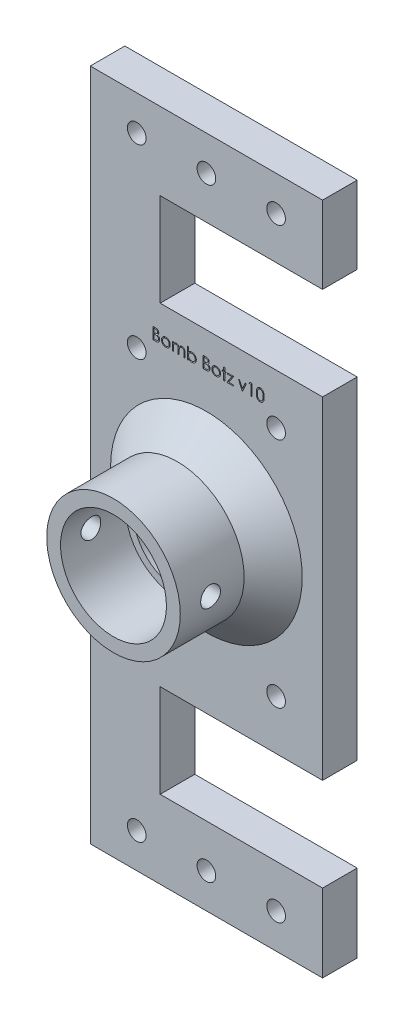
SolidWorks part; units mm, degrees
ref_plane "Front Plane" through (0, 0, 0) normal (0, 0, 1) x (1, 0, 0)
ref_plane "Top Plane" through (0, 0, 0) normal (0, 1, 0) x (1, 0, 0)
ref_plane "Right Plane" through (0, 0, 0) normal (1, 0, 0) x (0, 0, -1)
sketch "Sketch1" plane through (0, 0, 0) normal (0, 0, 1) x (1, 0, 0)
  line L5 (-31.75, 92.075) -> (31.75, 92.075)
  line L6 (-31.75, 92.075) -> (-31.75, -92.075)
  line L7 (-31.75, -92.075) -> (31.75, -92.075)
  line L8 (31.75, 92.075) -> (31.75, -92.075)
  line L9 (-31.75, 92.075) -> (31.75, -92.075) construction
  line L10 (-31.75, -92.075) -> (31.75, 92.075) construction
  point P5 (0, 0)
  dimension "D1" = 63.5
  dimension "D2" = 184.15
extrude "Boss-Extrude1" add sketch "Sketch1" along normal blind 4.7625 and the other way blind 4.699
sketch "Sketch3" plane through (0, 0, 4.7625) normal (0, 0, 1) x (1, 0, 0)
  circle A0 centre (0, 0) radius 6.35
  dimension "D1" = 12.7
extrude "Cut-Extrude1" cut sketch "Sketch3" against normal blind 0.508
sketch "Sketch4" plane through (0, 0, 4.7625) normal (0, 0, 1) x (1, 0, 0)
  circle A0 centre (0, 0) radius 18.2562
  dimension "D1" = 36.5125
extrude "Boss-Extrude2" add sketch "Sketch4" along normal blind 38.1 contours A0
sketch "Sketch5" plane through (0, 0, 42.8625) normal (0, 0, 1) x (1, 0, 0)
  circle A0 centre (0, 0) radius 12.4619
  dimension "D1" = 24.9237
extrude "Cut-Extrude2" cut sketch "Sketch5" against normal blind 38.1 contours A0
sketch "Sketch7" plane through (0, 0, 42.8625) normal (0, 0, 1) x (1, 0, 0)
  circle A0 centre (0, 0) radius 14.2875
  dimension "D1" = 28.575
extrude "Cut-Extrude3" cut sketch "Sketch7" against normal blind 30.48
hole_wizard "#10 Clearance Hole1" positions "Sketch8" profile "Sketch9" hole size "#10" standard "ANSI Inch" end condition up to next
sketch "Sketch8" plane through (0, 0, 4.7625) normal (0, 0, 1) x (1, 0, 0)
  line L0 (31.75, 92.075) -> (-31.75, 92.075) construction
  line L1 (31.75, -92.075) -> (31.75, 92.075) construction
  line L2 (-31.75, 92.075) -> (-31.75, -92.075) construction
  line L3 (-31.75, -92.075) -> (31.75, -92.075) construction
  point P0 (-19.05, 82.55)
  point P2 (-19.05, -82.55)
  point P4 (19.05, -82.55)
  point P6 (19.05, 82.55)
  point P23 (-19.05, 31.75)
  point P26 (-19.05, -31.75)
  point P28 (19.05, -31.75)
  point P30 (19.05, 31.75)
  point P31 (0, 82.55)
  point P33 (0, -82.55)
  dimension "D1" = 9.525
  dimension "D2" = 12.7
  dimension "D3" = 9.525
  dimension "D4" = 12.7
  dimension "D5" = 9.525
  dimension "D6" = 12.7
  dimension "D7" = 12.7
  dimension "D8" = 9.525
  dimension "D11" = 50.8
  dimension "D12" = 50.8
  dimension "D13" = 50.8
  dimension "D14" = 50.8
sketch "Sketch9" plane through (-19.05, 82.55, 4.7625) normal (1, 0, 0) x (0, -1, 0)
  line L0 (0, 0) -> (0, 9.4615)
  line L1 (0, 9.4615) -> (2.5527, 9.4615)
  line L2 (2.5527, 9.4615) -> (2.5527, 0)
  line L5 (2.5527, 0) -> (0, 0)
  line L11 (0, -6.35) -> (0, 107.95) construction
  dimension "Thru Hole Dia." = 5.1054
  dimension "Thru Hole Depth" = 9.4615
sketch "Sketch10" plane through (0, 0, 4.7625) normal (0, 0, 1) x (1, 0, 0)
  line L0 (31.75, 41.275) -> (-31.75, 41.275)
  line L1 (31.75, -92.075) -> (31.75, 92.075) construction
  line L2 (-31.75, 92.075) -> (-31.75, -92.075) construction
  line L3 (31.75, -41.275) -> (-31.75, -41.275)
  point P8 (-31.75, 0)
  dimension "D1" = 41.275
  dimension "D2" = 41.275
sketch "Sketch13" plane through (0, 0, 42.8625) normal (0, 0, 1) x (1, 0, 0)
  circle A0 centre (0, 0) radius 14.478
  dimension "D1" = 28.956
extrude "Cut-Extrude4" cut sketch "Sketch13" against normal up to surface (30.48 mm away) up to face at (14.2875, 0, 12.3825)
sketch "Sketch14" plane through (0, 0, 42.8625) normal (0, 0, 1) x (1, 0, 0)
  circle A0 centre (0, 0) radius 18.2562
extrude "Cut-Extrude5" cut sketch "Sketch14" against normal blind 12.7
sketch "Sketch15" plane through (0, -92.075, 0) normal (0, -1, 0) x (-1, 0, 0)
hole_wizard "#3 (0.213) Diameter Hole1" positions "3DSketch7" profile "Sketch22" hole size "#3" standard "ANSI Inch" end condition through all
sketch3d "3DSketch7"
  point P0 (18.2562, 0, 21.8735)
sketch "Sketch22" plane through (18.2562, 0, 21.8735) normal (0, 1, 0) x (0, 0, -1)
  line L0 (0, 0) -> (0, 50.0063)
  line L1 (0, 50.0063) -> (2.7051, 50.0063)
  line L2 (2.7051, 50.0063) -> (2.7051, 0)
  line L5 (2.7051, 0) -> (0, 0)
  line L11 (0, -6.35) -> (0, 107.95) construction
  dimension "Thru Hole Dia." = 5.4102
  dimension "Thru Hole Depth" = 50.0063
hole_wizard "CBORE for M6 Hex Head Bolt1" positions "Sketch25" profile "Sketch26" counterbore size "M6" standard "ANSI Metric" end condition through all
sketch "Sketch25" plane through (0, 0, -4.699) normal (0, 0, -1) x (-1, 0, 0)
  line L0 (-31.75, 41.275) -> (31.75, 41.275) construction
  line L1 (-31.75, -41.275) -> (31.75, -41.275) construction
  point P0 (0, -58.039)
  point P2 (0, 58.039)
  dimension "D1" = 16.764
  dimension "D2" = 16.764
sketch "Sketch26" plane through (0, -58.039, -4.699) normal (1, 0, 0) x (0, 1, 0)
  line L0 (0, 0) -> (0, 34.8615)
  line L1 (0, 34.8615) -> (3.5, 34.8615)
  line L3 (3.5, 34.8615) -> (3.5, 4.38)
  line L4 (3.5, 4.38) -> (7.275, 4.38)
  line L5 (7.275, 4.38) -> (7.275, 0)
  line L7 (7.275, 0) -> (0, 0)
  line L11 (0, -6.35) -> (0, 107.95) construction
  dimension "Thru Hole Dia." = 7
  dimension "Thru Hole Depth" = 34.8615
  dimension "C'Bore Dia." = 14.55
  dimension "C'Bore Depth" = 4.38
sketch "Sketch28" plane through (0, 0, 4.7625) normal (0, 0, 1) x (1, 0, 0)
  text T0 "Bomb Botz v10"
extrude "Boss-Extrude4" add sketch "Sketch28" against normal blind 1.27
chamfer "Chamfer1" distance 7.9375 distance2 7.9375 1 edges at (18.2562, 0, 4.7625)
sketch "Sketch29" plane through (0, 0, 4.7625) normal (0, 0, 1) x (1, 0, 0)
  text T0 "Bomb Botz v10"
extrude "Cut-Extrude6" cut sketch "Sketch29" against normal blind 1.27
sketch "Sketch30" plane through (0, 0, 4.7625) normal (0, 0, 1) x (1, 0, 0)
  line L1 (-12.6371, 70.9327) -> (12.6371, 70.9327)
  line L2 (-12.6371, 70.9327) -> (-12.6371, 45.483)
  line L3 (-12.6371, 45.483) -> (12.6371, 45.483)
  line L4 (12.6371, 70.9327) -> (12.6371, 45.483)
  line L5 (-12.6371, 70.9327) -> (12.6371, 45.483) construction
  line L6 (-12.6371, 45.483) -> (12.6371, 70.9327) construction
  point P0 (0, 58.2079)
extrude "Cut-Extrude7" cut sketch "Sketch30" against normal through all
sketch "Sketch31" plane through (0, 0, 4.7625) normal (0, 0, 1) x (1, 0, 0)
  line L1 (-12.639, -45.3001) -> (12.639, -45.3001)
  line L2 (-12.639, -45.3001) -> (-12.639, -70.7779)
  line L3 (-12.639, -70.7779) -> (12.639, -70.7779)
  line L4 (12.639, -45.3001) -> (12.639, -70.7779)
  line L5 (-12.639, -45.3001) -> (12.639, -70.7779) construction
  line L6 (-12.639, -70.7779) -> (12.639, -45.3001) construction
  point P0 (0, -58.039)
extrude "Cut-Extrude8" cut sketch "Sketch31" against normal through all
sketch "Sketch32" plane through (0, 0, 4.7625) normal (0, 0, 1) x (1, 0, 0)
  line L0 (12.639, -45.3001) -> (12.639, -70.7779)
  line L1 (12.639, -45.3001) -> (31.7854, -45.3001)
  line L2 (12.639, -70.7779) -> (31.7854, -70.7779)
  line L3 (31.7854, -45.3001) -> (31.7854, -70.7779)
extrude "Cut-Extrude10" cut sketch "Sketch32" against normal through all
sketch "Sketch33" plane through (0, 0, 4.7625) normal (0, 0, 1) x (1, 0, 0)
  line L0 (12.6371, 70.9327) -> (12.6371, 45.483)
  line L1 (12.6371, 70.9327) -> (31.75, 70.9327)
  line L2 (12.6371, 45.483) -> (31.75, 45.483)
  line L3 (31.75, 70.9327) -> (31.75, 45.483)
extrude "Cut-Extrude11" cut sketch "Sketch33" against normal through all
